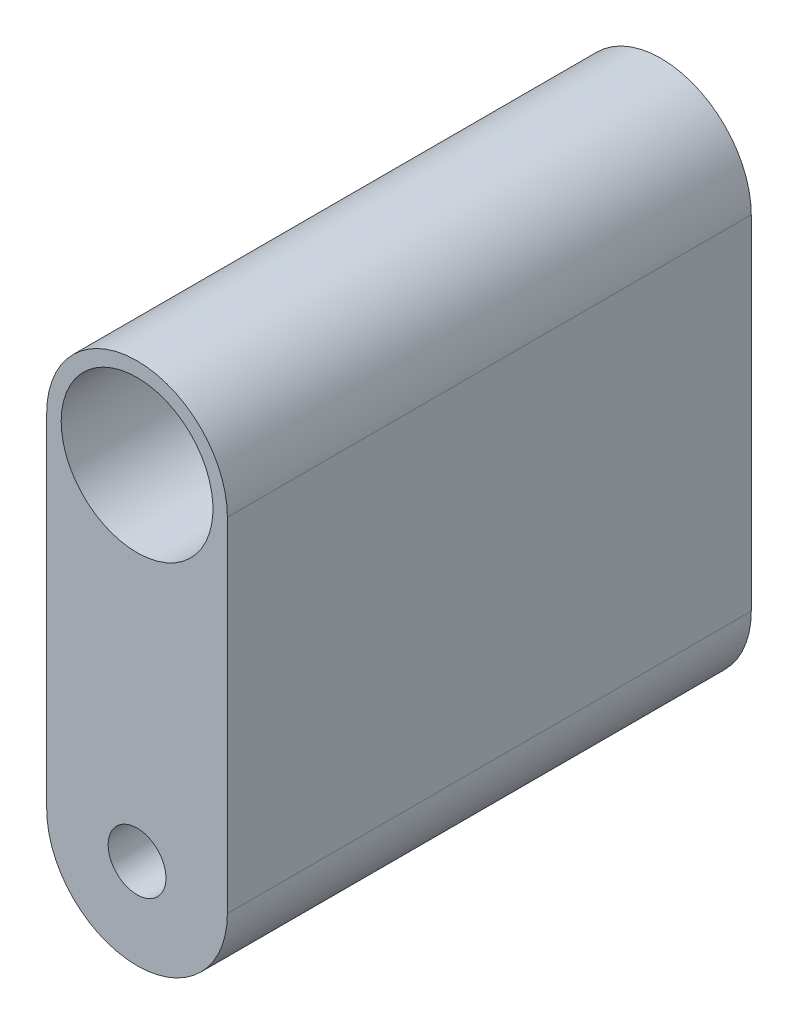
SolidWorks part; units mm, degrees
ref_plane "Front Plane" through (0, 0, 0) normal (1, 0, 0) x (0, 1, 0)
ref_plane "Top Plane" through (0, 0, 0) normal (0, 0, 1) x (0, 1, 0)
ref_plane "Right Plane" through (0, 0, 0) normal (0, 1, 0) x (-1, 0, 0)
sketch "Sketch3" plane through (0, 0, 0) normal (0, 0, 1) x (0, 1, 0)
  line L0 (0, 0) -> (19, 0) construction
  line L1 (0, 5) -> (19, 5)
  line L2 (0, -5) -> (19, -5)
  arc A0 (0, 5) -> (0, -5) centre (0, 0) ccw
  arc A1 (19, -5) -> (19, 5) centre (19, 0) ccw
  circle A2 centre (0, 0) radius 1.6
  circle A3 centre (19, 0) radius 4.2
  point P3 (9.5, 0)
  dimension "D1" = 8.4
  dimension "D2" = 3.2
  dimension "D4" = 29
  dimension "D3" = 10
extrude "Boss-Extrude1" add sketch "Sketch3" along normal blind 29
